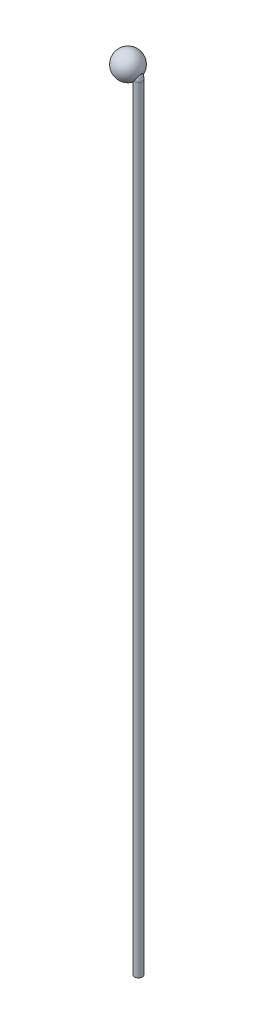
SolidWorks part; units mm, degrees
ref_plane "Front Plane" through (0, 0, 0) normal (0, 0, 1) x (1, 0, 0)
ref_plane "Top Plane" through (0, 0, 0) normal (0, 1, 0) x (1, 0, 0)
ref_plane "Right Plane" through (0, 0, 0) normal (1, 0, 0) x (0, 0, -1)
sketch "Sketch1" plane through (0, 0, 0) normal (1, 0, 0) x (0, 0, -1)
  line L0 (0, 0.165) -> (0, -0.165) construction
  circle A0 centre (0, 0) radius 0.15
  dimension "D1" = 0.3
sketch "Sketch3" plane through (0, 0, 0) normal (0, 0, 1) x (1, 0, 0)
  line L0 (0, 0) -> (0.1, 0)
  line L1 (0.4, -0.3) -> (0.4, -30)
  arc A0 (0.4, -0.3) -> (0.1, 0) centre (0.1, -0.3) ccw
  point P6 (0.4, 0)
  dimension "D3" = 0.3
  dimension "D1" = 30
  dimension "D2" = 0.4
sweep "Sweep1" add profiles "Sketch1" path "Sketch3"
sketch "Sketch4" plane through (0, 0, 0) normal (-1, 0, 0) x (0, 0, 1)
  line L0 (0, 0.5) -> (0, -0.5)
  arc A0 (0, 0.5) -> (0, -0.5) centre (0, 0) ccw
  dimension "D1" = 1
revolve "Revolve2" add sketch "Sketch4" angle 360 about L0
sketch "Sketch5" plane through (0, 0, 0) normal (0, 0, 1) x (1, 0, 0)
  line L0 (0.4, -0.3) -> (0.4, -30) construction
  line L1 (0.4, -0.3) -> (0.4, -30)
